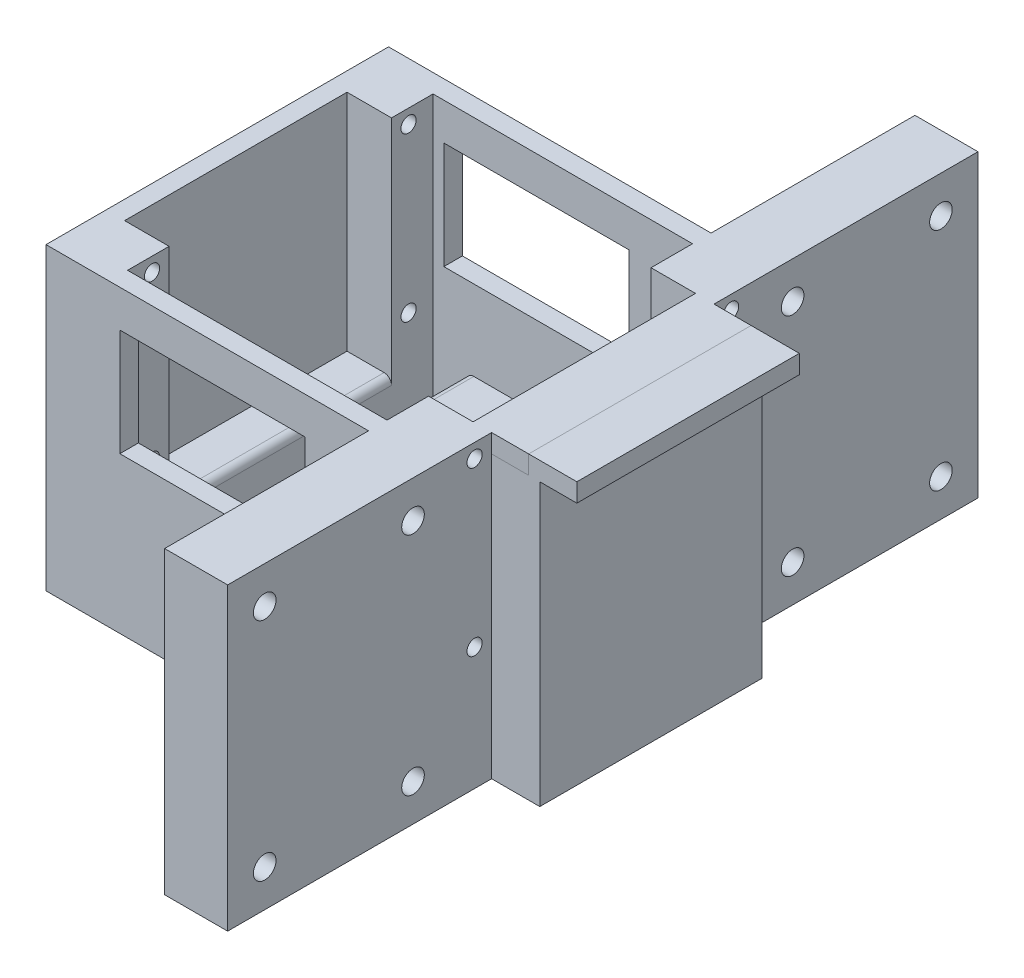
SolidWorks part; units mm, degrees
ref_plane "Front Plane" through (0, 0, 0) normal (0, 0, 1) x (1, 0, 0)
ref_plane "Top Plane" through (0, 0, 0) normal (0, 1, 0) x (1, 0, 0)
ref_plane "Right Plane" through (0, 0, 0) normal (1, 0, 0) x (0, 0, -1)
sketch "Sketch1" plane through (0, 0, 0) normal (0, 0, 1) x (1, 0, 0)
  line L0 (-541.5637, 173.6139) -> (-541.5637, 143.8639) construction
  line L1 (-542.0637, 173.6139) -> (-544.5637, 173.6139)
  line L2 (-541.5637, 143.8639) -> (-535.5637, 143.8639) construction
  line L3 (-535.5637, 143.8639) -> (-535.5637, 138.2639) construction
  line L4 (-535.5637, 138.2639) -> (-532.0637, 138.2639) construction
  line L5 (-532.0637, 138.2639) -> (-532.0637, 143.8639) construction
  line L6 (-532.0637, 143.8639) -> (-519.0637, 143.8639) construction
  line L7 (-541.5637, 151.7706) -> (-495.5637, 151.7706) construction
  line L8 (-542.0637, 173.6139) -> (-542.0637, 143.3639)
  line L9 (-542.0637, 143.3639) -> (-536.0637, 143.3639)
  line L10 (-536.0637, 143.3639) -> (-536.0637, 137.7639)
  line L11 (-536.0637, 137.7639) -> (-531.5637, 137.7639)
  line L12 (-531.5637, 137.7639) -> (-531.5637, 143.3639)
  line L13 (-544.5637, 173.6139) -> (-544.5637, 133.1707)
  line L14 (-542.0637, 153.3892) -> (-519.0637, 153.3892) construction
  line L15 (-531.5637, 143.3639) -> (-519.0637, 143.3639)
  line L16 (-531.5637, 143.3639) -> (-519.0637, 143.3639) construction
  line L17 (-495.0637, 173.6139) -> (-495.0637, 143.3639)
  line L18 (-519.0637, 153.3892) -> (-519.0637, 143.3639) construction
  line L19 (-542.0637, 173.6139) -> (-492.5637, 173.6139) construction
  line L20 (-495.5637, 173.6139) -> (-495.5637, 143.8639) construction
  line L21 (-495.5637, 143.8639) -> (-501.5637, 143.8639) construction
  line L22 (-501.5637, 143.8639) -> (-501.5637, 138.2639) construction
  line L23 (-501.5637, 138.2639) -> (-506.0637, 138.2639) construction
  line L24 (-506.0637, 138.2639) -> (-506.0637, 143.8639) construction
  line L25 (-506.0637, 143.8639) -> (-519.0637, 143.8639) construction
  line L26 (-495.0637, 143.3639) -> (-501.0637, 143.3639)
  line L27 (-501.0637, 143.3639) -> (-501.0637, 137.7639)
  line L28 (-501.0637, 137.7639) -> (-506.5637, 137.7639)
  line L29 (-506.5637, 137.7639) -> (-506.5637, 143.3639)
  line L30 (-506.5637, 143.3639) -> (-519.0637, 143.3639)
  line L31 (-544.5637, 133.1707) -> (-492.5637, 133.1707)
  line L32 (-492.5637, 133.1707) -> (-492.5637, 173.6139)
  line L33 (-492.5637, 173.6139) -> (-495.0637, 173.6139)
  dimension "D2" = 46
  dimension "D3" = 23
  dimension "D4" = 0.5
  dimension "D5" = 2.5
  dimension "D6" = 2.5
  dimension "D7" = 5.6
  dimension "D1" = 0.5
extrude "Boss-Extrude1" add sketch "Sketch1" along normal blind 30 contours L32 L33 L17 L26 L27 L28 L29 L30 L15 L12 L11 L10 L9 L8 L1 L13 L31
sketch "Sketch2" plane through (-544.5637, 0, 0) normal (-1, 0, 0) x (0, 0, 1)
  line L0 (30, 173.6139) -> (0, 173.6139) construction
  line L1 (-5.6, 173.6139) -> (35.6, 173.6139) construction
  line L2 (-5.6, 173.6139) -> (-5.6, 133.1707) construction
  line L3 (-5.6, 133.1707) -> (35.6, 133.1707) construction
  line L4 (35.6, 173.6139) -> (35.6, 133.1707) construction
  line L5 (30, 153.3923) -> (0, 153.3923) construction
  line L6 (30, 173.6139) -> (30, 133.1707) construction
  line L7 (0, 173.6139) -> (0, 133.1707) construction
  line L8 (15, 153.3923) -> (15, 173.6139) construction
  line L9 (30, 133.1707) -> (0, 133.1707) construction
  line L10 (-5.6, 173.6139) -> (0, 173.6139)
  line L11 (-5.6, 173.6139) -> (-5.6, 133.1707)
  line L12 (-5.6, 133.1707) -> (0, 133.1707)
  line L13 (0, 173.6139) -> (0, 133.1707)
  line L14 (35.6, 173.6139) -> (30, 173.6139)
  line L15 (35.6, 173.6139) -> (35.6, 133.1707)
  line L16 (35.6, 133.1707) -> (30, 133.1707)
  line L17 (30, 173.6139) -> (30, 133.1707)
  line L18 (0, 170.1387) -> (30, 170.1387) construction
  circle A0 centre (-2.3, 171.7139) radius 1.025
  circle A1 centre (-2.3, 149.7139) radius 1.025
  circle A2 centre (32.3, 149.7139) radius 1.025
  circle A3 centre (32.3, 171.7139) radius 1.025
  point P18 (-2.3, 171.7139)
  point P19 (-2.3, 149.7139)
  point P21 (32.3, 149.7139)
  point P23 (32.3, 171.7139)
  dimension "D9" = 2.05
  dimension "D10" = 2.05
  dimension "D11" = 2.05
  dimension "D12" = 2.05
  dimension "D1" = 0
  dimension "D2" = 0
  dimension "D3" = 41.2
  dimension "D4" = 20.6
  dimension "D5" = 1.9
  dimension "D6" = 3.3
  dimension "D7" = 23.9
  dimension "D8" = 3.3
  dimension "D13" = 30
extrude "Boss-Extrude2" add sketch "Sketch2" against normal blind 8.5
sketch "Sketch4" plane through (0, 0, 0) normal (0, 0, -1) x (-1, 0, 0)
  line L0 (536.0637, 133.1707) -> (492.5637, 133.1707) construction
  line L1 (506.5637, 143.3639) -> (531.5637, 143.3639)
  line L2 (506.5637, 143.3639) -> (506.5637, 133.1707)
  line L3 (506.5637, 133.1707) -> (531.5637, 133.1707)
  line L4 (531.5637, 143.3639) -> (531.5637, 133.1707)
extrude "Boss-Extrude3" add sketch "Sketch4" along normal up to surface (5.6 mm away) up to face at (-540.3137, 153.3923, -5.6)
sketch "Sketch5" plane through (0, 0, 30) normal (0, 0, 1) x (1, 0, 0)
  line L0 (-536.0637, 133.1707) -> (-492.5637, 133.1707) construction
  line L1 (-531.5637, 143.3639) -> (-506.5637, 143.3639)
  line L2 (-531.5637, 143.3639) -> (-531.5637, 133.1707)
  line L3 (-531.5637, 133.1707) -> (-506.5637, 133.1707)
  line L4 (-506.5637, 143.3639) -> (-506.5637, 133.1707)
extrude "Boss-Extrude4" add sketch "Sketch5" along normal up to surface (5.6 mm away) up to face at (-540.3137, 153.3923, 35.6)
fillet "Fillet2" radius 1 2 edges at (-506.5637, 143.3639, 15) (-531.5637, 143.3639, 15)
sketch "Sketch6" plane through (-492.5637, 0, 0) normal (1, 0, 0) x (0, 0, -1)
  line L1 (-35.6, 173.6139) -> (-30, 173.6139)
  line L2 (-35.6, 173.6139) -> (-35.6, 133.1707)
  line L3 (-35.6, 133.1707) -> (-30, 133.1707)
  line L4 (-30, 173.6139) -> (-30, 133.1707)
  line L5 (0, 173.6139) -> (5.6, 173.6139)
  line L6 (0, 173.6139) -> (0, 133.1707)
  line L7 (0, 133.1707) -> (5.6, 133.1707)
  line L8 (5.6, 173.6139) -> (5.6, 133.1707)
  circle A0 centre (-32.3, 171.7139) radius 1.025
  circle A1 centre (2.3, 171.7139) radius 1.025
  circle A2 centre (2.3, 149.7139) radius 1.025
  circle A3 centre (-32.3, 149.7139) radius 1.025
  point P12 (-32.3, 171.7139)
  point P13 (-32.3, 149.7139)
  point P15 (2.3, 149.7139)
  point P17 (2.3, 171.7139)
  dimension "D1" = 2.05
  dimension "D2" = 2.05
  dimension "D3" = 2.05
  dimension "D4" = 2.05
extrude "Boss-Extrude5" add sketch "Sketch6" against normal up to surface (8.5 mm away) up to face at (-501.0637, 140.5639, 15)
fillet "Fillet3" radius 1 2 edges at (-536.0637, 143.3639, 15) (-501.0637, 143.3639, 15)
sketch "Sketch8" plane through (-492.5637, 0, 0) normal (1, 0, 0) x (0, 0, -1)
  line L0 (-15, 173.6139) -> (-15, 133.1707) construction
  line L1 (-35.6, 173.6139) -> (5.6, 173.6139) construction
  line L2 (-35.6, 133.1707) -> (5.6, 133.1707) construction
  line L3 (-15, 153.3923) -> (5.6, 153.3923) construction
  line L4 (5.6, 133.1707) -> (5.6, 173.6139) construction
  circle A0 centre (-15, 153.3923) radius 2.1
  point P11 (-15, 153.3923)
  dimension "D1" = 4.2
extrude "Cut-Extrude1" cut sketch "Sketch8" against normal blind 8.5 contours A0
sketch "Sketch9" plane through (0, 173.6139, 0) normal (0, 1, 0) x (1, 0, 0)
  line L0 (-501.0637, -35.6) -> (-501.0637, -30) construction
  line L1 (-501.0637, 5.6) -> (-492.5637, 5.6)
  line L2 (-501.0637, 5.6) -> (-501.0637, 35.6)
  line L3 (-501.0637, 35.6) -> (-492.5637, 35.6)
  line L4 (-492.5637, 5.6) -> (-492.5637, 35.6)
  line L5 (-501.0637, -35.6) -> (-492.5637, -35.6)
  line L6 (-501.0637, -35.6) -> (-501.0637, -65.6)
  line L7 (-501.0637, -65.6) -> (-492.5637, -65.6)
  line L8 (-492.5637, -35.6) -> (-492.5637, -65.6)
  line L9 (-501.0637, -35.6) -> (-492.5637, -35.6) construction
  dimension "D1" = 30
  dimension "D2" = 8.5
  dimension "D3" = 30
  dimension "D4" = 8.5
extrude "Boss-Extrude6" add sketch "Sketch9" against normal up to surface (40.4433 mm away) up to face at (-518.7637, 133.1707, 15)
sketch "Sketch10" plane through (-501.0637, 0, 0) normal (-1, 0, 0) x (0, 0, 1)
  line L0 (15, 173.6139) -> (15, 133.1707) construction
  line L1 (35.6, 173.6139) -> (-5.6, 173.6139) construction
  line L2 (35.6, 133.1707) -> (-5.6, 133.1707) construction
  line L3 (-35.6, 153.3923) -> (65.6, 153.3923) construction
  line L4 (-35.6, 133.1707) -> (-35.6, 173.6139) construction
  line L5 (65.6, 133.1707) -> (65.6, 173.6139) construction
  line L6 (40.6, 168.6139) -> (40.6, 138.1707) construction
  line L7 (35.6, 173.6139) -> (65.6, 173.6139) construction
  line L8 (35.6, 173.6139) -> (35.6, 133.1707) construction
  line L9 (35.6, 133.1707) -> (65.6, 133.1707) construction
  line L10 (65.6, 173.6139) -> (65.6, 133.1707) construction
  line L11 (40.6, 138.1707) -> (60.6, 138.1707) construction
  line L12 (60.6, 168.6139) -> (60.6, 138.1707) construction
  line L13 (40.6, 168.6139) -> (60.6, 168.6139) construction
  circle A0 centre (40.6, 168.6139) radius 1.525
  circle A1 centre (60.6, 168.6139) radius 1.525
  circle A2 centre (60.6, 138.1707) radius 1.525
  circle A3 centre (40.6, 138.1707) radius 1.525
  circle A4 centre (-30.6, 168.6139) radius 1.525
  circle A5 centre (-30.6, 138.1707) radius 1.525
  circle A6 centre (-10.6, 138.1707) radius 1.525
  circle A7 centre (-10.6, 168.6139) radius 1.525
  dimension "D2" = 3.05
  dimension "D3" = 3.05
  dimension "D4" = 3.05
  dimension "D5" = 3.05
  dimension "D1" = 5
extrude "Cut-Extrude2" cut sketch "Sketch10" against normal through all
sketch "Sketch11" plane through (0, 173.6139, 0) normal (0, 1, 0) x (1, 0, 0)
  line L0 (-492.5637, -65.6) -> (-492.5637, 35.6) construction
  line L1 (-492.5637, 0) -> (-487.5637, 0)
  line L2 (-492.5637, 0) -> (-492.5637, -30)
  line L3 (-492.5637, -30) -> (-487.5637, -30)
  line L4 (-487.5637, 0) -> (-487.5637, -30)
  dimension "D1" = 5
  dimension "D2" = 30
extrude "Boss-Extrude7" add sketch "Sketch11" against normal blind 2.5
sketch "Sketch12" plane through (-492.5637, 0, 0) normal (1, 0, 0) x (0, 0, -1)
  line L0 (-65.6, 133.1707) -> (35.6, 133.1707) construction
  line L1 (-30, 171.1139) -> (0, 171.1139)
  line L2 (-30, 171.1139) -> (-30, 133.1707)
  line L3 (-30, 133.1707) -> (0, 133.1707)
  line L4 (0, 171.1139) -> (0, 133.1707)
  dimension "D1" = 0
  dimension "D2" = 30
extrude "Boss-Extrude8" add sketch "Sketch12" along normal up to surface (5 mm away) separate body contours L2 L3 L4 L1 up to face at (-487.5637, 172.3639, 15)
sketch "Sketch13" plane through (-487.5637, 0, 0) normal (1, 0, 0) x (0, 0, -1)
  line L1 (-30, 173.6139) -> (0, 173.6139)
  line L2 (-30, 173.6139) -> (-30, 133.1707)
  line L3 (-30, 133.1707) -> (0, 133.1707)
  line L4 (0, 173.6139) -> (0, 133.1707)
extrude "Boss-Extrude9" add sketch "Sketch13" along normal blind 1.5
sketch "Sketch15" plane through (-486.0637, 0, 0) normal (1, 0, 0) x (0, 0, -1)
  line L1 (-30, 173.6139) -> (0, 173.6139)
  line L2 (-30, 173.6139) -> (-30, 171.1139)
  line L3 (-30, 171.1139) -> (0, 171.1139)
  line L4 (0, 173.6139) -> (0, 171.1139)
  dimension "D1" = 2.5
extrude "Boss-Extrude10" add sketch "Sketch15" along normal blind 5
sketch "Sketch17" plane through (-501.0637, 0, 0) normal (-1, 0, 0) x (0, 0, 1)
  line L0 (30, 133.1707) -> (65.6, 133.1707) construction
  line L1 (35.6, 173.6139) -> (38.1, 173.6139)
  line L2 (35.6, 173.6139) -> (35.6, 133.1707)
  line L3 (35.6, 133.1707) -> (38.1, 133.1707)
  line L4 (38.1, 173.6139) -> (38.1, 133.1707)
  line L5 (-35.6, 133.1707) -> (0, 133.1707) construction
  line L6 (-5.6, 173.6139) -> (-8.1, 173.6139)
  line L7 (-5.6, 173.6139) -> (-5.6, 133.1707)
  line L8 (-5.6, 133.1707) -> (-8.1, 133.1707)
  line L9 (-8.1, 173.6139) -> (-8.1, 133.1707)
  dimension "D1" = 2.5
  dimension "D2" = 2.5
extrude "Boss-Extrude11" add sketch "Sketch17" along normal up to surface (43.5 mm away) up to face at (-544.5637, 153.3923, 15)
sketch "Sketch18" plane through (0, 0, 38.1) normal (0, 0, 1) x (1, 0, 0)
  line L1 (-534.6057, 168.6139) -> (-509.6057, 168.6139)
  line L2 (-534.6057, 168.6139) -> (-534.6057, 154.1707)
  line L3 (-534.6057, 154.1707) -> (-509.6057, 154.1707)
  line L4 (-509.6057, 168.6139) -> (-509.6057, 154.1707)
  line L5 (-544.5637, 133.1707) -> (-501.0637, 133.1707) construction
  line L6 (-501.0637, 133.1707) -> (-501.0637, 173.6139) construction
  line L7 (-544.5637, 173.6139) -> (-501.0637, 173.6139) construction
  dimension "D1" = 5
  dimension "D2" = 25
  dimension "D3" = 21
  dimension "D4" = 8.542
extrude "Cut-Extrude5" cut sketch "Sketch18" against normal blind 60
sketch "Sketch19" plane through (0, 133.1707, 0) normal (0, -1, 0) x (1, 0, 0)
  line L1 (-544.5637, 38.1) -> (-501.0637, 38.1)
  line L2 (-544.5637, 38.1) -> (-544.5637, -8.1)
  line L3 (-544.5637, -8.1) -> (-501.0637, -8.1)
  line L4 (-501.0637, 38.1) -> (-501.0637, -8.1)
extrude "Boss-Extrude12" add sketch "Sketch19" against normal up to surface (4.5933 mm away) up to face at (-533.8137, 137.7639, 15)
sketch "Sketch22" plane through (-486.0637, 0, 0) normal (1, 0, 0) x (0, 0, -1)
  line L0 (-15, 173.6139) -> (-15, 133.1707) construction
  line L1 (0, 173.6139) -> (-30, 173.6139) construction
  line L2 (-30, 133.1707) -> (0, 133.1707) construction
  line L3 (-15, 153.3923) -> (0, 153.3923) construction
  line L4 (0, 133.1707) -> (0, 171.1139) construction
  circle A0 centre (-15, 153.3923) radius 2.05
  dimension "D1" = 4.1
extrude "Boss-Extrude15" add sketch "Sketch22" against normal blind 9
other "Save Bodies1"
